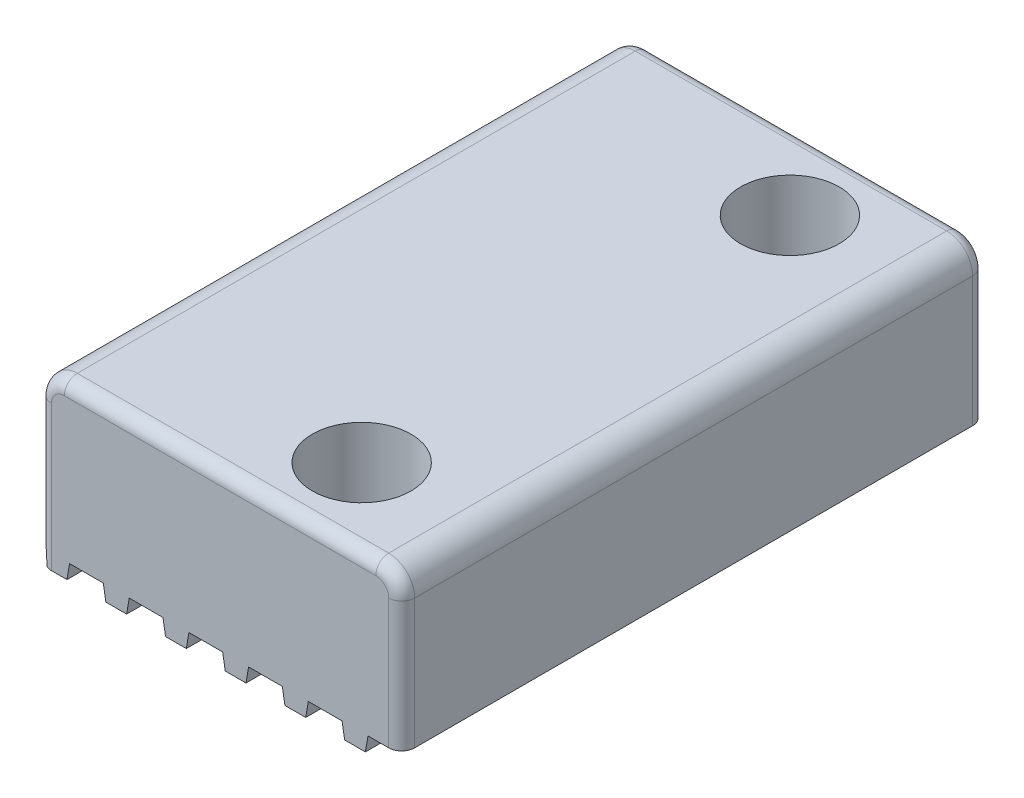
SolidWorks part; units mm, degrees
ref_plane "Front Plane" through (0, 0, 0) normal (0, 0, 1) x (1, 0, 0)
ref_plane "Top Plane" through (0, 0, 0) normal (0, 1, 0) x (1, 0, 0)
ref_plane "Right Plane" through (0, 0, 0) normal (1, 0, 0) x (0, 0, -1)
sketch "Sketch1" plane through (0, 0, 0) normal (0, 0, 1) x (1, 0, 0)
  line L0 (167.9467, 62.1447) -> (167.9467, 67.1447)
  line L1 (181.9467, 62.1447) -> (180.6467, 62.1447)
  line L2 (180.6467, 62.1447) -> (180.5467, 61.5587)
  line L3 (180.5467, 61.5587) -> (179.7467, 61.5587)
  line L4 (179.6467, 62.1447) -> (179.7467, 61.5587)
  line L5 (180.1467, 61.6265) -> (180.1467, 61.5587) construction
  line L6 (177.3467, 62.1447) -> (177.4467, 61.5587)
  line L7 (178.2467, 61.5587) -> (177.4467, 61.5587)
  line L8 (178.3467, 62.1447) -> (178.2467, 61.5587)
  line L9 (179.6467, 62.1447) -> (178.3467, 62.1447)
  line L10 (175.0467, 62.1447) -> (175.1467, 61.5587)
  line L11 (175.9467, 61.5587) -> (175.1467, 61.5587)
  line L12 (176.0467, 62.1447) -> (175.9467, 61.5587)
  line L13 (177.3467, 62.1447) -> (176.0467, 62.1447)
  line L14 (172.7467, 62.1447) -> (172.8467, 61.5587)
  line L15 (173.6467, 61.5587) -> (172.8467, 61.5587)
  line L16 (173.7467, 62.1447) -> (173.6467, 61.5587)
  line L17 (175.0467, 62.1447) -> (173.7467, 62.1447)
  line L18 (170.4467, 62.1447) -> (170.5467, 61.5587)
  line L19 (171.3467, 61.5587) -> (170.5467, 61.5587)
  line L20 (171.4467, 62.1447) -> (171.3467, 61.5587)
  line L21 (172.7467, 62.1447) -> (171.4467, 62.1447)
  line L22 (168.1467, 62.1447) -> (168.2467, 61.5587)
  line L23 (169.0467, 61.5587) -> (168.2467, 61.5587)
  line L24 (169.1467, 62.1447) -> (169.0467, 61.5587)
  line L25 (170.4467, 62.1447) -> (169.1467, 62.1447)
  line L29 (168.1467, 62.1447) -> (167.9467, 62.1447)
  line L43 (1182.2209, 61.9406) -> (172.5645, 61.9406) construction
  line L87 (180.9467, 68.1447) -> (168.9467, 68.1447)
  line L88 (181.9467, 62.1447) -> (181.9467, 67.1447)
  line L127 (166.8467, 62.1447) -> (166.7467, 61.5587) [skipped]
  line L128 (165.8467, 62.1447) -> (165.9467, 61.5587) [skipped]
  line L129 (166.7467, 61.5587) -> (165.9467, 61.5587) [skipped]
  arc A0 (180.9467, 68.1447) -> (181.9467, 67.1447) centre (180.9467, 67.1447) cw
  arc A1 (167.9467, 67.1447) -> (168.9467, 68.1447) centre (168.9467, 67.1447) cw
  point P12 (180.1467, 61.5587)
  dimension "D1" = 1
  dimension "D2" = 5
  dimension "D3" = 12
  dimension "D4" = 0.8
  dimension "D5" = 2.3
  dimension "D6" = 1.3
  dimension "D7" = 7
extrude "Boss-Extrude1" add sketch "Sketch1" against normal blind 22.5
sketch "Sketch2" plane through (0, 68.1447, 0) normal (0, 1, 0) x (1, 0, 0)
  circle A2 centre (177.4038, 3) radius 1.9
  circle A4 centre (177.4038, 19.5) radius 1.9
extrude "Cut-Extrude1" cut sketch "Sketch2" against normal through all
fillet "Fillet1" radius 0.5 10 edges at (181.9467, 64.6447, -22.5) (181.6538, 67.8518, -22.5) (167.9467, 64.6447, -22.5) (168.2396, 67.8518, -22.5) (181.9467, 64.6447, 0) (181.6538, 67.8518, 0) (167.9467, 64.6447, 0) (168.2396, 67.8518, 0) (174.9467, 68.1447, -22.5) (174.9467, 68.1447, 0)
